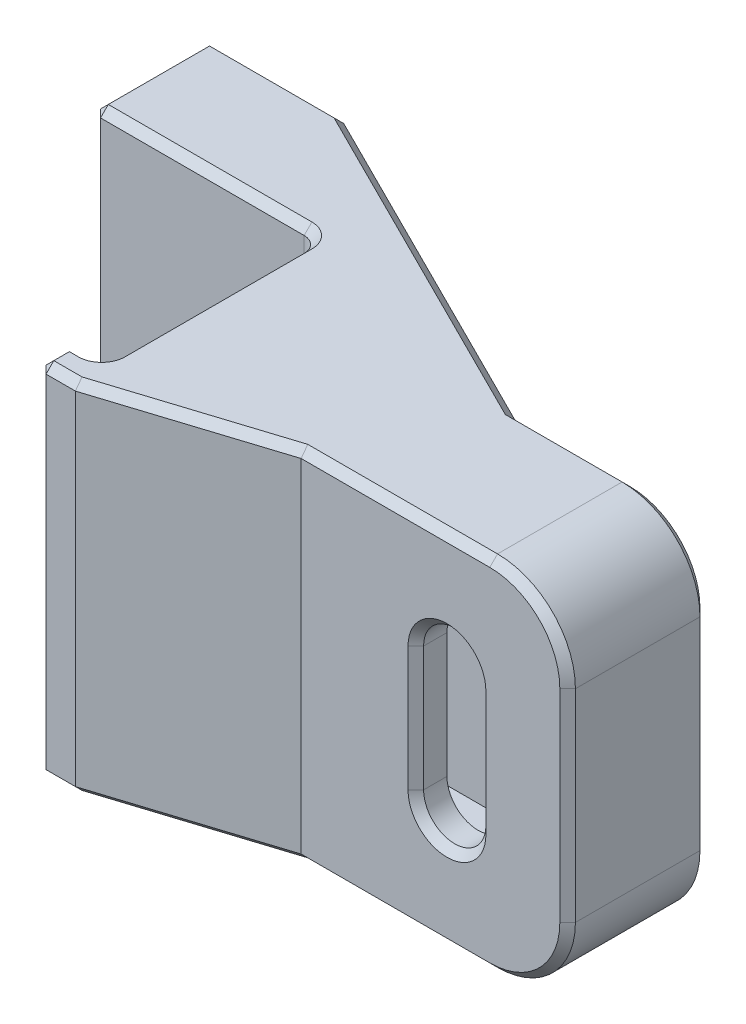
SolidWorks part; units mm, degrees
material "PET"
ref_plane "Front Plane" through (0, 0, 0) normal (0, 0, 1) x (1, 0, 0)
ref_plane "Top Plane" through (0, 0, 0) normal (0, 1, 0) x (1, 0, 0)
ref_plane "Right Plane" through (0, 0, 0) normal (1, 0, 0) x (0, 0, -1)
sketch "Reference" plane through (0, 0, 0) normal (0, 1, 0) x (1, 0, 0)
  line L0 (0, 0) -> (4, 0) construction
  line L1 (4, 0) -> (26, 7) construction
  line L2 (26, 7) -> (56, 7) construction
  line L3 (56, 7) -> (56, 15) construction
  line L4 (56, 15) -> (26, 15) construction
  line L5 (26, 15) -> (4, 26) construction
  line L6 (4, 26) -> (0, 26) construction
  point P8 (0, 0)
  point P10 (30, 15)
  point P11 (4, 19.1439)
  point P12 (0, 26)
  dimension "D1" = 4
  dimension "D2" = 26
  dimension "D3" = 30
  dimension "D4" = 8
  dimension "D5" = 15
  dimension "D6" = 11
sketch "Sketch2" plane through (0, 0, 0) normal (0, 1, 0) x (1, 0, 0)
  line L0 (61, 20) -> (26.2361, 20) construction
  line L1 (36.2361, 20) -> (-7.7639, 42)
  line L2 (-25, 42) -> (-25, 27)
  line L44 (0, -5) -> (4.7763, -5)
  line L45 (4.7763, -5) -> (26.7763, 2)
  line L46 (26.7763, 2) -> (61, 2)
  line L47 (61, 2) -> (61, 20)
  line L48 (61, 20) -> (36.2361, 20)
  line L49 (0, -5) -> (0, -1)
  line L50 (-25, 42) -> (-7.7639, 42)
  line L51 (4.2361, 27) -> (0, 27)
  line L52 (26.2361, 16) -> (4.2361, 27)
  line L53 (57, 16) -> (26.2361, 16)
  line L54 (57, 6) -> (57, 16)
  line L55 (26.1553, 6) -> (57, 6)
  line L56 (4.1553, -1) -> (26.1553, 6)
  line L57 (0, -1) -> (4.1553, -1)
  line L58 (4.2361, 27) -> (-25, 27)
  line L59 (26.2361, 16) -> (4.2361, 27)
  line L60 (57, 16) -> (26.2361, 16)
  line L61 (57, 6) -> (57, 16)
  line L62 (26.1553, 6) -> (57, 6)
  line L63 (4.1553, -1) -> (26.1553, 6)
  line L64 (0, -1) -> (4.1553, -1)
  point P8 (-12.5666, 27)
  dimension "D3" = 12
  dimension "D4" = 25
  dimension "D5" = 15
  dimension "D1" = 1
  dimension "D2" = 4
extrude "Create internal geometry" add sketch "Sketch2" along normal blind 38
sketch "Sketch4" plane through (0, 0, -2) normal (0, 0, 1) x (1, 0, 0)
  line L0 (45.5, 27) -> (45.5, 11) construction
  line L1 (49.5, 27) -> (49.5, 11)
  line L2 (41.5, 27) -> (41.5, 11)
  line L3 (61, 19) -> (-25, 19) construction
  line L4 (61, 38) -> (61, 0) construction
  line L5 (-25, 38) -> (-25, 0) construction
  line L6 (61, 38) -> (61, 0) construction
  arc A0 (49.5, 27) -> (41.5, 27) centre (45.5, 27) ccw
  arc A1 (41.5, 11) -> (49.5, 11) centre (45.5, 11) ccw
  point P2 (45.5, 19)
  point P13 (0, 0)
  dimension "D1" = 8
  dimension "D2" = 16
  dimension "D3" = 11.5
extrude "Cut shackle hole" cut sketch "Sketch4" against normal through all
ref_plane "Mid plane" through (0, 19, 0) normal (0, 1, 0) x (1, 0, 0)
sketch "Sketch3" plane through (0, 38, 0) normal (0, 1, 0) x (1, 0, 0)
  line L0 (-25, 27) -> (4.2361, 27) construction
  line L1 (-25, 42) -> (-25, 27) construction
  line L2 (-7.7639, 42) -> (-25, 42) construction
  line L3 (36.2361, 20) -> (-7.7639, 42) construction
  line L4 (61, 20) -> (36.2361, 20) construction
  line L5 (61, 2) -> (61, 20) construction
  line L6 (26.7763, 2) -> (61, 2) construction
  line L7 (4.7763, -5) -> (26.7763, 2) construction
  line L8 (0, -5) -> (4.7763, -5) construction
  line L9 (4.1553, -1) -> (0, -1) construction
  line L10 (0, -1) -> (0, -5) construction
  line L11 (-25, 27) -> (2.1553, 27)
  line L12 (-25, 42) -> (-25, 27)
  line L13 (-7.7639, 42) -> (-25, 42)
  line L14 (36.2361, 20) -> (-7.7639, 42)
  line L15 (61, 20) -> (36.2361, 20)
  line L16 (61, 2) -> (61, 20)
  line L17 (26.7763, 2) -> (61, 2)
  line L18 (4.7763, -5) -> (26.7763, 2)
  line L19 (0, -5) -> (4.7763, -5)
  line L20 (2.1553, -1) -> (0, -1)
  line L21 (0, -1) -> (0, -5)
  line L22 (4.1553, 25) -> (4.1553, 1)
  arc A0 (4.1553, 1) -> (2.1553, -1) centre (2.1553, 1) cw
  arc A1 (4.1553, 25) -> (2.1553, 27) centre (2.1553, 25) ccw
  dimension "D1" = 2
extrude "Cap top end" add sketch "Sketch3" along normal blind 4
mirror "Mirror top cap to bottom" about plane through (0, 19, 0) normal (0, 1, 0) of "Cap top end"
fillet "Round corners" radius 10 4 edges at (61, 42, -11) (61, -4, -11) (57, 38, -11) (57, 0, -11)
chamfer "Unnecessary chamfers" distance 1 angle 45 44 edges at (61, 19, -2) (61, 19, -20) (58.0711, -1.0711, -20) (58.0711, -1.0711, -2) (58.0711, 39.0711, -2) (58.0711, 39.0711, -20) (43.618, -4, -20) (14.2361, -4, -31) (-16.382, -4, -42) (-25, -4, -34.5) (-11.4224, -4, -27) (3.5695, -4, -26.4142) (4.1553, -4, -13) (3.5695, -4, 0.4142) (1.0776, -4, 1) (0, -4, 3) (38.8881, -4, -2) (15.7763, -4, 1.5) (2.3881, -4, 5) (38.8881, 42, -2) (15.7763, 42, 1.5) (2.3881, 42, 5) (0, 19, 5) (0, 42, 3) (0, 19, 1) (1.0776, 42, 1) (3.5695, 42, 0.4142) (4.1553, 42, -13) (3.5695, 42, -26.4142) (-11.4224, 42, -27) (-25, 19, -27) (-25, 42, -34.5) (43.618, 42, -20) (14.2361, 42, -31) (-16.382, 42, -42) (-25, 19, -42) (49.5, 19, -20) (45.5, 31, -20) (45.5, 7, -20) (41.5, 19, -20) (45.5, 31, -2) (41.5, 19, -2) (49.5, 19, -2) (45.5, 7, -2)
